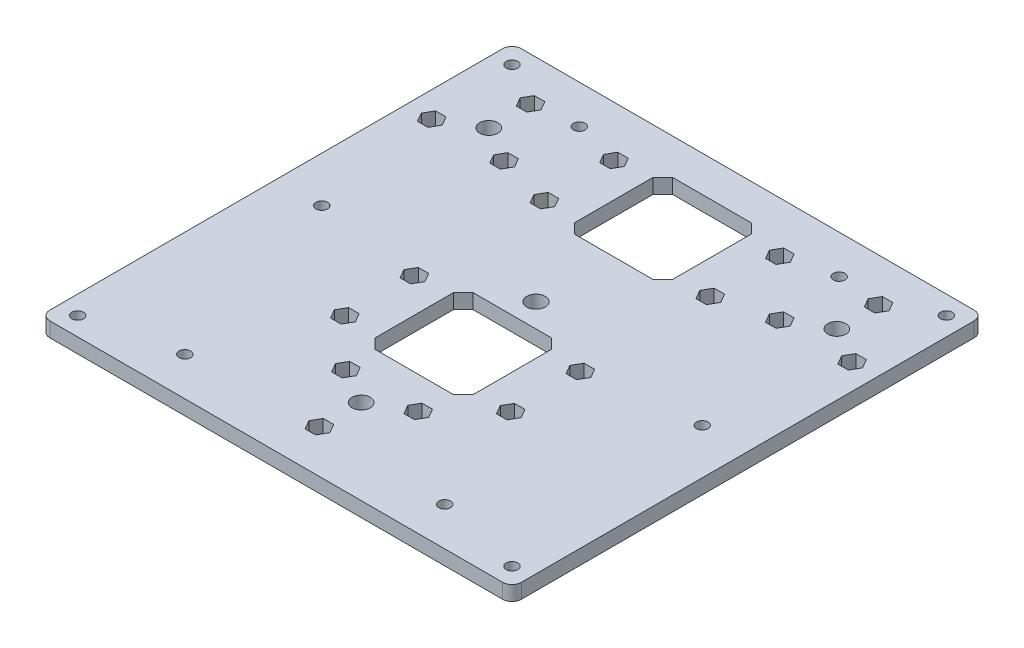
SolidWorks part; units mm, degrees
ref_plane "Plan de face" through (0, 0, 0) normal (0, 0, 1) x (1, 0, 0)
ref_plane "Plan de dessus" through (0, 0, 0) normal (0, 1, 0) x (1, 0, 0)
ref_plane "Plan de droite" through (0, 0, 0) normal (1, 0, 0) x (0, 0, -1)
sketch "Esquisse1" plane through (0, 0, 0) normal (0, 1, 0) x (1, 0, 0)
  line L1 (-101.6, -101.6) -> (101.6, -101.6)
  line L2 (-101.6, -101.6) -> (-101.6, 101.6)
  line L3 (-101.6, 101.6) -> (101.6, 101.6)
  line L4 (101.6, -101.6) -> (101.6, 101.6)
  line L5 (-101.6, -101.6) -> (101.6, 101.6) construction
  line L6 (-101.6, 101.6) -> (101.6, -101.6) construction
  point P0 (0, 0)
  dimension "D1" = 203.2
extrude "Boss.-Extru.1" add sketch "Esquisse1" along normal blind 6.35
sketch "Esquisse2" plane through (0, 6.35, 0) normal (0, 1, 0) x (1, 0, 0)
  circle A0 centre (-75, 65) radius 3.925
  circle A1 centre (75, 65) radius 3.925
  circle A2 centre (0, -65) radius 3.925
  dimension "D1" = 7.85
  dimension "D2" = 65
  dimension "D3" = 65
  dimension "D4" = 150
  dimension "D5" = 75
extrude "Enlèv. mat.-Extru.1" cut sketch "Esquisse2" against normal through all
sketch "Esquisse3" plane through (0, 6.35, 0) normal (0, 1, 0) x (1, 0, 0)
  line L0 (-16.9781, 86.15) -> (-21.15, 81.9781)
  line L1 (-21.15, 81.9781) -> (-21.15, 48.0219)
  line L2 (-21.15, 48.0219) -> (-16.9781, 43.85)
  line L3 (-16.9781, 43.85) -> (16.9781, 43.85)
  line L4 (16.9781, 43.85) -> (21.15, 48.0219)
  line L5 (21.15, 48.0219) -> (21.15, 81.9781)
  line L6 (21.15, 81.9781) -> (16.9781, 86.15)
  line L7 (16.9781, 86.15) -> (-16.9781, 86.15)
  line L9 (-75, 65) -> (75, 65) construction
  point P8 (0, 43.85)
  point P11 (0, 86.15)
  point P12 (-21.15, 65)
  point P13 (21.15, 65)
  dimension "D1" = 5.9
  dimension "D2" = 42.3
extrude "Enlèv. mat.-Extru.2" cut sketch "Esquisse3" against normal through all
sketch "Esquisse5" plane through (0, 6.35, 0) normal (0, 1, 0) x (1, 0, 0)
  line L0 (-31.3967, 49.85) -> (-33.6483, 45.95)
  line L1 (-35.9, 49.85) -> (-35.9, 54.8456) construction
  line L2 (-33.6483, 45.95) -> (-38.1517, 45.95)
  line L3 (-38.1517, 45.95) -> (-40.4033, 49.85)
  line L4 (-40.4033, 49.85) -> (-38.1517, 53.75)
  line L5 (-38.1517, 53.75) -> (-33.6483, 53.75)
  line L6 (-33.6483, 53.75) -> (-31.3967, 49.85)
  line L7 (-35.9, 49.85) -> (-37.3663, 49.85) construction
  point P2 (-35.9, 53.75)
  dimension "D1" = 7.8
  dimension "D2" = 7.8
  dimension "D3" = 7.8
extrude "Enlèv. mat.-Extru.5" cut sketch "Esquisse5" against normal through all
sketch "Esquisse7" plane through (0, 6.35, 0) normal (0, 1, 0) x (1, 0, 0)
  line L0 (-33.6483, 75.95) -> (-38.1517, 75.95)
  line L1 (-38.1517, 75.95) -> (-40.4033, 79.85)
  line L2 (-40.4033, 79.85) -> (-38.1517, 83.75)
  line L3 (-38.1517, 83.75) -> (-33.6483, 83.75)
  line L4 (-33.6483, 83.75) -> (-31.3967, 79.85)
  line L6 (-31.3967, 79.85) -> (-33.6483, 75.95)
  line L8 (-35.9, 79.85) -> (-37.5148, 79.85) construction
  line L9 (-35.9, 79.85) -> (-35.9, 74.6708) construction
  point P8 (-35.9, 75.95)
  dimension "D1" = 7.8
  dimension "D2" = 7.8
  dimension "D3" = 7.8
extrude "Enlèv. mat.-Extru.6" cut sketch "Esquisse7" against normal through all
sketch "Esquisse8" plane through (0, 6.35, 0) normal (0, 1, 0) x (1, 0, 0)
  line L0 (37.8517, 45.95) -> (33.3483, 45.95)
  line L1 (33.3483, 45.95) -> (31.0967, 49.85)
  line L2 (31.0967, 49.85) -> (33.3483, 53.75)
  line L3 (33.3483, 53.75) -> (37.8517, 53.75)
  line L4 (37.8517, 53.75) -> (40.1033, 49.85)
  line L5 (40.1033, 49.85) -> (37.8517, 45.95)
  line L6 (35.6, 49.85) -> (36.7872, 49.85) construction
  line L7 (35.6, 49.85) -> (35.6, 61.6399) construction
  point P9 (35.6, 45.95)
  dimension "D1" = 7.8
  dimension "D2" = 7.8
  dimension "D3" = 7.8
extrude "Enlèv. mat.-Extru.7" cut sketch "Esquisse8" against normal through all
sketch "Esquisse9" plane through (0, 6.35, 0) normal (0, 1, 0) x (1, 0, 0)
  line L0 (37.8517, 75.95) -> (33.3483, 75.95)
  line L1 (33.3483, 75.95) -> (31.0967, 79.85)
  line L2 (31.0967, 79.85) -> (33.3483, 83.75)
  line L3 (33.3483, 83.75) -> (37.8517, 83.75)
  line L4 (37.8517, 83.75) -> (40.1033, 79.85)
  line L5 (40.1033, 79.85) -> (37.8517, 75.95)
  line L6 (35.6, 79.85) -> (35.6, 71.0093) construction
  line L7 (35.6, 71.0093) -> (35.6, 79.85) construction
  line L8 (35.6, 79.85) -> (36.558, 79.85) construction
  point P11 (35.6, 83.75)
  dimension "D1" = 7.8
  dimension "D2" = 7.8
  dimension "D3" = 7.8
extrude "Enlèv. mat.-Extru.8" cut sketch "Esquisse9" against normal through all
sketch "Esquisse10" plane through (0, 6.35, 0) normal (0, 1, 0) x (1, 0, 0)
  line L0 (101.6, 101.6) -> (-101.6, 101.6) construction
  line L1 (-11.0851, -56) -> (-13.3368, -52.1)
  line L2 (-13.3368, -52.1) -> (-17.8401, -52.1)
  line L3 (-17.8401, -52.1) -> (-20.0918, -56)
  line L4 (-20.0918, -56) -> (-17.8401, -59.9)
  line L5 (-17.8401, -59.9) -> (-13.3368, -59.9)
  line L6 (-13.3368, -59.9) -> (-11.0851, -56)
  line L7 (11.0851, -56) -> (13.3368, -59.9)
  line L8 (13.3368, -59.9) -> (17.8401, -59.9)
  line L9 (17.8401, -59.9) -> (20.0918, -56)
  line L10 (20.0918, -56) -> (17.8401, -52.1)
  line L11 (17.8401, -52.1) -> (13.3368, -52.1)
  line L12 (13.3368, -52.1) -> (11.0851, -56)
  line L13 (-4.5033, -83) -> (-2.2517, -86.9)
  line L14 (-2.2517, -86.9) -> (2.2517, -86.9)
  line L15 (2.2517, -86.9) -> (4.5033, -83)
  line L16 (4.5033, -83) -> (2.2517, -79.1)
  line L17 (2.2517, -79.1) -> (-2.2517, -79.1)
  line L18 (-2.2517, -79.1) -> (-4.5033, -83)
  line L19 (-63.9163, 55.9992) -> (-61.6647, 52.0992)
  line L20 (-61.6647, 52.0992) -> (-57.1613, 52.0992)
  line L21 (-57.1613, 52.0992) -> (-54.9097, 55.9992)
  line L22 (-54.9097, 55.9992) -> (-57.1613, 59.8992)
  line L23 (-57.1613, 59.8992) -> (-61.6647, 59.8992)
  line L24 (-61.6647, 59.8992) -> (-63.9163, 55.9992)
  line L25 (-95.0933, 55.9992) -> (-92.8416, 52.0992)
  line L26 (-92.8416, 52.0992) -> (-88.3383, 52.0992)
  line L27 (-88.3383, 52.0992) -> (-86.0866, 55.9992)
  line L28 (-86.0866, 55.9992) -> (-88.3383, 59.8992)
  line L29 (-88.3383, 59.8992) -> (-92.8416, 59.8992)
  line L30 (-92.8416, 59.8992) -> (-95.0933, 55.9992)
  line L31 (-79.5048, 82.9992) -> (-77.2531, 79.0992)
  line L32 (-77.2531, 79.0992) -> (-72.7498, 79.0992)
  line L33 (-72.7498, 79.0992) -> (-70.4981, 82.9992)
  line L34 (-70.4981, 82.9992) -> (-72.7498, 86.8992)
  line L35 (-72.7498, 86.8992) -> (-77.2531, 86.8992)
  line L36 (-77.2531, 86.8992) -> (-79.5048, 82.9992)
  line L37 (54.9082, 56) -> (57.1599, 52.1)
  line L38 (57.1599, 52.1) -> (61.6632, 52.1)
  line L39 (61.6632, 52.1) -> (63.9149, 56)
  line L40 (63.9149, 56) -> (61.6632, 59.9)
  line L41 (61.6632, 59.9) -> (57.1599, 59.9)
  line L42 (57.1599, 59.9) -> (54.9082, 56)
  line L43 (95.0918, 56) -> (92.8401, 59.9)
  line L44 (92.8401, 59.9) -> (88.3368, 59.9)
  line L45 (88.3368, 59.9) -> (86.0851, 56)
  line L46 (86.0851, 56) -> (88.3368, 52.1)
  line L47 (88.3368, 52.1) -> (92.8401, 52.1)
  line L48 (92.8401, 52.1) -> (95.0918, 56)
  line L49 (70.4967, 83) -> (72.7483, 79.1)
  line L50 (72.7483, 79.1) -> (77.2517, 79.1)
  line L51 (77.2517, 79.1) -> (79.5033, 83)
  line L52 (79.5033, 83) -> (77.2517, 86.9)
  line L53 (77.2517, 86.9) -> (72.7483, 86.9)
  line L54 (72.7483, 86.9) -> (70.4967, 83)
  circle A0 centre (-15.5885, -56) radius 3.9 construction
  circle A1 centre (15.5885, -56) radius 3.9 construction
  circle A2 centre (0, -83) radius 3.9 construction
  circle A3 centre (-59.413, 55.9992) radius 3.9 construction
  circle A4 centre (-90.5899, 55.9992) radius 3.9 construction
  circle A5 centre (-75.0015, 82.9992) radius 3.9 construction
  circle A6 centre (59.4115, 56) radius 3.9 construction
  circle A7 centre (90.5885, 56) radius 3.9 construction
  circle A8 centre (75, 83) radius 3.9 construction
  dimension "D1" = 7.8
extrude "Enlèv. mat.-Extru.9" cut sketch "Esquisse10" against normal through all
sketch "Esquisse11" plane through (0, 6.35, 0) normal (0, 1, 0) x (1, 0, 0)
  circle A0 centre (93.6, 93.6) radius 2.5
  circle A1 centre (-93.6, 93.6) radius 2.5
  circle A2 centre (-93.6, -93.6) radius 2.5
  circle A3 centre (93.6, -93.6) radius 2.5
extrude "Enlèv. mat.-Extru.10" cut sketch "Esquisse11" against normal through all
sketch "Esquisse12" plane through (0, 6.35, 0) normal (0, 1, 0) x (1, 0, 0)
  circle A0 centre (0, 10.325) radius 4
  circle A1 centre (0, 10.325) radius 4 construction
extrude "Enlèv. mat.-Extru.11" cut sketch "Esquisse12" against normal through all
sketch "Esquisse13" plane through (0, 0, 0) normal (0, -1, 0) x (1, 0, 0)
  circle A0 centre (56, -85) radius 2.5
  circle A1 centre (82, 0) radius 2.5
  circle A2 centre (82, 0) radius 2.5 construction
  circle A3 centre (56, -85) radius 2.5 construction
extrude "Enlèv. mat.-Extru.12" cut sketch "Esquisse13" against normal through all
mirror "Symétrie1" about plane through (0, 0, 0) normal (0, 0, 1) of "Enlèv. mat.-Extru.12"
mirror "Symétrie2" about plane through (0, 0, 0) normal (1, 0, 0) of "Symétrie1", "Enlèv. mat.-Extru.12"
fillet "Congé3" radius 4 4 edges at (101.6, 3.175, -101.6) (101.6, 3.175, 101.6) (-101.6, 3.175, 101.6) (-101.6, 3.175, -101.6)
sketch "Esquisse14" plane through (0, 6.35, 0) normal (0, 1, 0) x (1, 0, 0)
  line L0 (16.9781, -42.15) -> (-16.9781, -42.15)
  line L1 (-16.9781, -42.15) -> (-21.15, -37.9781)
  line L2 (-21.15, -37.9781) -> (-21.15, -4.0219)
  line L3 (-21.15, -4.0219) -> (-16.9781, 0.15)
  line L4 (-16.9781, 0.15) -> (16.9781, 0.15)
  line L5 (16.9781, 0.15) -> (21.15, -4.0219)
  line L6 (21.15, -4.0219) -> (21.15, -37.9781)
  line L7 (21.15, -37.9781) -> (16.9781, -42.15)
  line L8 (21.15, -4.0219) -> (16.9781, 0.15) construction
  line L10 (-21.15, -4.0219) -> (-21.15, -37.9781) construction
  line L11 (-21.15, -37.9781) -> (-16.9781, -42.15) construction
  line L12 (16.9781, -42.15) -> (21.15, -37.9781) construction
extrude "Enlèv. mat.-Extru.13" cut sketch "Esquisse14" against normal through all
sketch "Esquisse15" plane through (0, 6.35, 0) normal (0, 1, 0) x (1, 0, 0)
  circle A0 centre (35.6, -36.15) radius 2.6
  circle A1 centre (35.6, -6.15) radius 2.6
  circle A2 centre (-35.9, -36.15) radius 2.6
  circle A3 centre (-35.9, -6.15) radius 2.6
  circle A4 centre (35.6, -36.15) radius 2.6 construction
extrude "Enlèv. mat.-Extru.14" cut sketch "Esquisse15" against normal through all
sketch "Esquisse16" plane through (0, 6.35, 0) normal (0, 1, 0) x (1, 0, 0)
  line L0 (33.3483, 45.95) -> (37.8517, 45.95) construction
  line L1 (31.0967, -36.15) -> (33.3483, -40.05)
  line L2 (33.3483, -40.05) -> (37.8517, -40.05)
  line L3 (37.8517, -40.05) -> (40.1033, -36.15)
  line L4 (40.1033, -36.15) -> (37.8517, -32.25)
  line L5 (37.8517, -32.25) -> (33.3483, -32.25)
  line L6 (33.3483, -32.25) -> (31.0967, -36.15)
  line L7 (31.0967, -6.15) -> (33.3483, -10.05)
  line L8 (33.3483, -10.05) -> (37.8517, -10.05)
  line L9 (37.8517, -10.05) -> (40.1033, -6.15)
  line L10 (40.1033, -6.15) -> (37.8517, -2.25)
  line L11 (37.8517, -2.25) -> (33.3483, -2.25)
  line L12 (33.3483, -2.25) -> (31.0967, -6.15)
  line L13 (-40.4033, -6.15) -> (-38.1517, -10.05)
  line L14 (-38.1517, -10.05) -> (-33.6483, -10.05)
  line L15 (-33.6483, -10.05) -> (-31.3967, -6.15)
  line L16 (-31.3967, -6.15) -> (-33.6483, -2.25)
  line L17 (-33.6483, -2.25) -> (-38.1517, -2.25)
  line L18 (-38.1517, -2.25) -> (-40.4033, -6.15)
  line L19 (-40.4033, -36.15) -> (-38.1517, -40.05)
  line L20 (-38.1517, -40.05) -> (-33.6483, -40.05)
  line L21 (-33.6483, -40.05) -> (-31.3967, -36.15)
  line L22 (-31.3967, -36.15) -> (-33.6483, -32.25)
  line L23 (-33.6483, -32.25) -> (-38.1517, -32.25)
  line L24 (-38.1517, -32.25) -> (-40.4033, -36.15)
  line L27 (-97.6, -101.6) -> (97.6, -101.6) construction
  circle A0 centre (35.6, -36.15) radius 3.9 construction
  circle A1 centre (35.6, -6.15) radius 3.9 construction
  circle A2 centre (-35.9, -6.15) radius 3.9 construction
  circle A3 centre (-35.9, -36.15) radius 3.9 construction
extrude "Enlèv. mat.-Extru.15" cut sketch "Esquisse16" against normal through all
